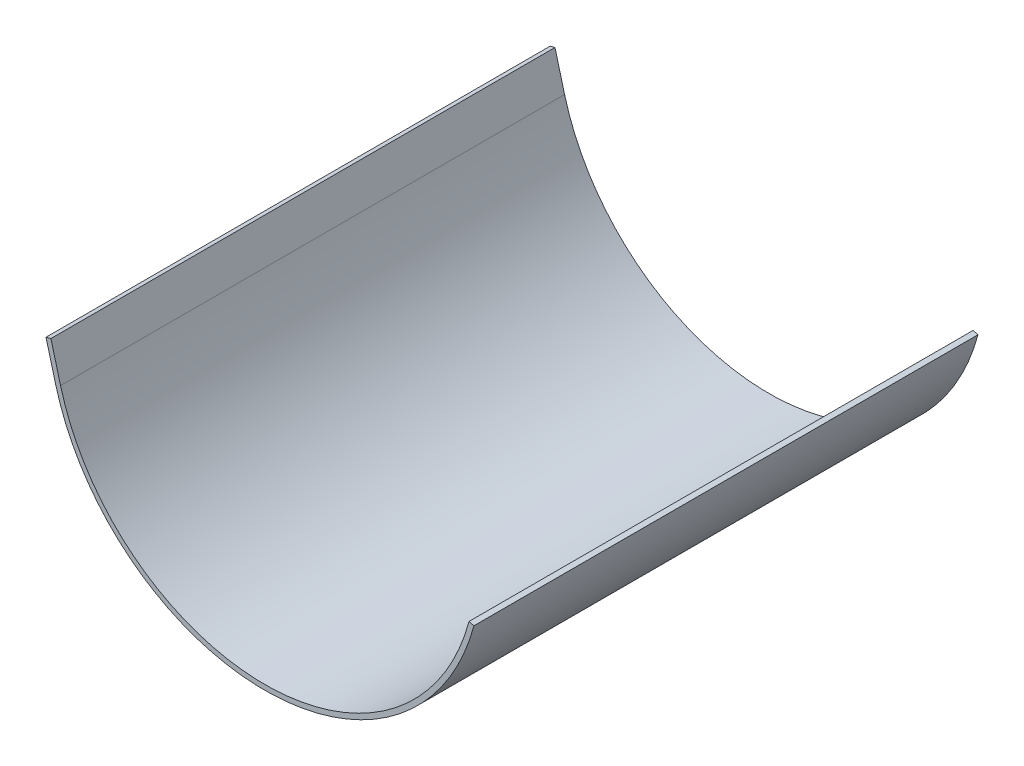
SolidWorks part; units mm, degrees
ref_plane "Front Plane" through (0, 0, 0) normal (0, 0, 1) x (1, 0, 0)
ref_plane "Top Plane" through (0, 0, 0) normal (0, 1, 0) x (1, 0, 0)
ref_plane "Right Plane" through (0, 0, 0) normal (1, 0, 0) x (0, 0, -1)
sketch "Sketch1" plane through (0, 0, 0) normal (0, 0, 1) x (1, 0, 0)
  line L3 (0, -62.5) -> (0, 0) construction
  line L4 (0, -55) -> (0, 55) construction
  line L5 (0, 0) -> (61.8193, -16.5644) construction
  line L9 (61.8193, -16.5644) -> (60.3704, -16.1762)
  line L10 (0, 0) -> (-61.8193, -16.5644) construction
  line L11 (-61.8193, -16.5644) -> (-60.3704, -16.1762)
  arc A0 (-60.3704, -16.1762) -> (60.3704, -16.1762) centre (0, 0) ccw
  arc A1 (-61.8193, -16.5644) -> (61.8193, -16.5644) centre (0, 0) ccw
  point P1 (0, 0)
  dimension "D3" = 62.5
  dimension "D4" = 64
  dimension "D1" = 1.5
  dimension "D2" = 75
extrude "Boss-Extrude1" add sketch "Sketch1" along normal mid plane 149
sketch "Sketch2" plane through (0, 0, 0) normal (-0.2588, 0.9659, 0) x (0.9659, 0.2588, 0)
  line L1 (-64, 74.5) -> (-62.5, 74.5)
  line L2 (-64, 74.5) -> (-64, -74.5)
  line L3 (-64, -74.5) -> (-62.5, -74.5)
  line L4 (-62.5, 74.5) -> (-62.5, -74.5)
extrude "Boss-Extrude2" add sketch "Sketch2" along normal blind 11
